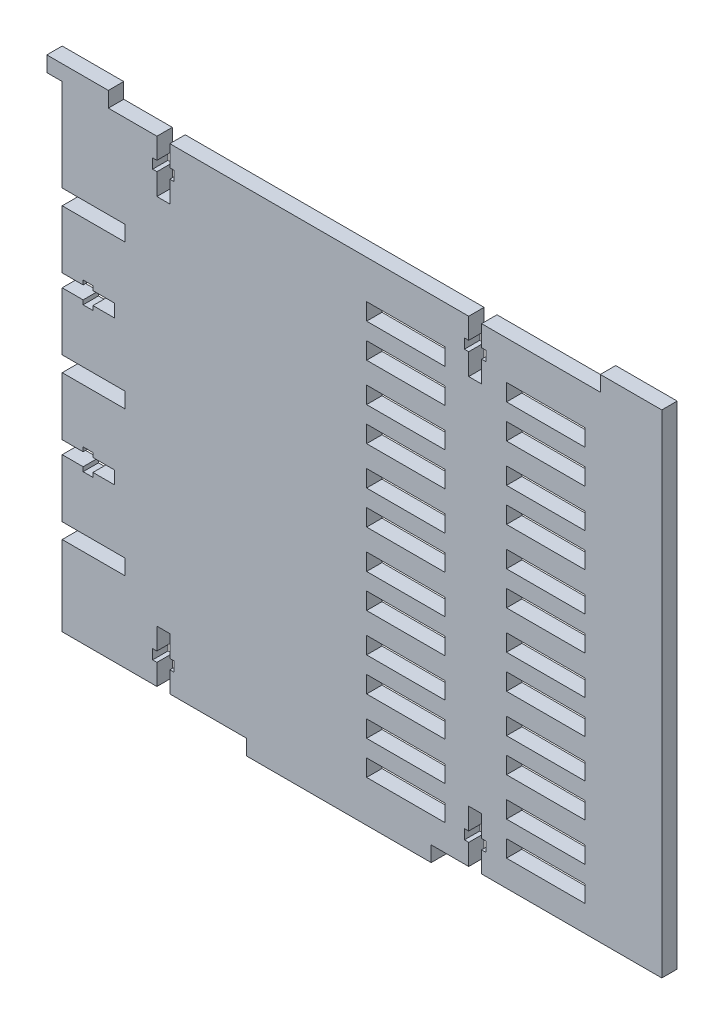
SolidWorks part; units mm, degrees
ref_plane "Front Plane" through (0, 0, 0) normal (0, 0, 1) x (1, 0, 0)
ref_plane "Top Plane" through (0, 0, 0) normal (0, 1, 0) x (1, 0, 0)
ref_plane "Right Plane" through (0, 0, 0) normal (1, 0, 0) x (0, 0, -1)
sketch "Sketch1" plane through (0, 0, 0) normal (0, 0, 1) x (1, 0, 0)
  line L0 (-45.5, 11) -> (-45.5, 16.5)
  line L1 (0, 0) -> (-25.5, 0)
  line L2 (0, 0) -> (0, 5.5)
  line L3 (0, 5.5) -> (-25.5, 5.5)
  line L4 (-25.5, 0) -> (-25.5, 5.5)
  line L5 (-45.5, 0) -> (-71, 0)
  line L6 (-45.5, 0) -> (-45.5, 5.5)
  line L7 (-45.5, 5.5) -> (-71, 5.5)
  line L8 (-71, 0) -> (-71, 5.5)
  line L9 (-45.5, 11) -> (-71, 11)
  line L10 (-71, 11) -> (-71, 16.5)
  line L11 (-45.5, 16.5) -> (-71, 16.5)
  line L12 (0, 11) -> (0, 16.5)
  line L13 (0, 11) -> (-25.5, 11)
  line L14 (-25.5, 11) -> (-25.5, 16.5)
  line L15 (0, 16.5) -> (-25.5, 16.5)
  line L16 (0, 23.5) -> (0, 29)
  line L17 (0, 23.5) -> (-25.5, 23.5)
  line L18 (-25.5, 23.5) -> (-25.5, 29)
  line L19 (0, 29) -> (-25.5, 29)
  line L20 (-45.5, 23.5) -> (-45.5, 29)
  line L21 (-45.5, 23.5) -> (-71, 23.5)
  line L22 (-71, 23.5) -> (-71, 29)
  line L23 (-45.5, 29) -> (-71, 29)
  line L24 (-45.5, 34.5) -> (-45.5, 40)
  line L25 (-45.5, 40) -> (-71, 40)
  line L26 (-71, 34.5) -> (-71, 40)
  line L27 (-45.5, 34.5) -> (-71, 34.5)
  line L28 (0, 34.5) -> (0, 40)
  line L29 (0, 40) -> (-25.5, 40)
  line L30 (-25.5, 34.5) -> (-25.5, 40)
  line L31 (0, 34.5) -> (-25.5, 34.5)
  line L32 (0, 47) -> (0, 52.5)
  line L33 (0, 47) -> (-25.5, 47)
  line L34 (-25.5, 47) -> (-25.5, 52.5)
  line L35 (0, 52.5) -> (-25.5, 52.5)
  line L36 (-45.5, 47) -> (-45.5, 52.5)
  line L37 (-45.5, 47) -> (-71, 47)
  line L38 (-71, 47) -> (-71, 52.5)
  line L39 (-45.5, 52.5) -> (-71, 52.5)
  line L40 (-45.5, 58) -> (-45.5, 63.5)
  line L41 (-45.5, 63.5) -> (-71, 63.5)
  line L42 (-71, 58) -> (-71, 63.5)
  line L43 (-45.5, 58) -> (-71, 58)
  line L44 (0, 58) -> (0, 63.5)
  line L45 (0, 63.5) -> (-25.5, 63.5)
  line L46 (-25.5, 58) -> (-25.5, 63.5)
  line L47 (0, 58) -> (-25.5, 58)
  line L48 (0, 70.5) -> (0, 76)
  line L49 (0, 70.5) -> (-25.5, 70.5)
  line L50 (-25.5, 70.5) -> (-25.5, 76)
  line L51 (0, 76) -> (-25.5, 76)
  line L52 (-45.5, 70.5) -> (-45.5, 76)
  line L53 (-45.5, 70.5) -> (-71, 70.5)
  line L54 (-71, 70.5) -> (-71, 76)
  line L55 (-45.5, 76) -> (-71, 76)
  line L56 (-45.5, 81.5) -> (-45.5, 87)
  line L57 (-45.5, 87) -> (-71, 87)
  line L58 (-71, 81.5) -> (-71, 87)
  line L59 (-45.5, 81.5) -> (-71, 81.5)
  line L60 (0, 81.5) -> (0, 87)
  line L61 (0, 87) -> (-25.5, 87)
  line L62 (-25.5, 81.5) -> (-25.5, 87)
  line L63 (0, 81.5) -> (-25.5, 81.5)
  line L64 (0, 94) -> (0, 99.5)
  line L65 (0, 94) -> (-25.5, 94)
  line L66 (-25.5, 94) -> (-25.5, 99.5)
  line L67 (0, 99.5) -> (-25.5, 99.5)
  line L68 (-45.5, 94) -> (-45.5, 99.5)
  line L69 (-45.5, 94) -> (-71, 94)
  line L70 (-71, 94) -> (-71, 99.5)
  line L71 (-45.5, 99.5) -> (-71, 99.5)
  line L72 (-45.5, 105) -> (-45.5, 110.5)
  line L73 (-45.5, 110.5) -> (-71, 110.5)
  line L74 (-71, 105) -> (-71, 110.5)
  line L75 (-45.5, 105) -> (-71, 105)
  line L76 (0, 105) -> (0, 110.5)
  line L77 (0, 110.5) -> (-25.5, 110.5)
  line L78 (-25.5, 105) -> (-25.5, 110.5)
  line L79 (0, 105) -> (-25.5, 105)
  line L80 (0, 117.5) -> (0, 123)
  line L81 (0, 117.5) -> (-25.5, 117.5)
  line L82 (-25.5, 117.5) -> (-25.5, 123)
  line L83 (0, 123) -> (-25.5, 123)
  line L84 (-45.5, 117.5) -> (-45.5, 123)
  line L85 (-45.5, 117.5) -> (-71, 117.5)
  line L86 (-71, 117.5) -> (-71, 123)
  line L87 (-45.5, 123) -> (-71, 123)
  line L88 (-45.5, 128.5) -> (-45.5, 134)
  line L89 (-45.5, 134) -> (-71, 134)
  line L90 (-71, 128.5) -> (-71, 134)
  line L91 (-45.5, 128.5) -> (-71, 128.5)
  line L92 (0, 128.5) -> (0, 134)
  line L93 (0, 134) -> (-25.5, 134)
  line L94 (-25.5, 128.5) -> (-25.5, 134)
  line L95 (0, 128.5) -> (-25.5, 128.5)
  line L96 (-155, 151.5) -> (-155, 146.5)
  line L97 (-175, 151.5) -> (-155, 151.5)
  line L98 (-175, 151.5) -> (-175, 146.5)
  line L100 (25, 151.5) -> (25, -8.5)
  line L101 (-155, 146.5) -> (5, 146.5)
  line L102 (5, 146.5) -> (5, 151.5)
  line L103 (-150, 71.5) -> (25, 71.5) construction
  line L107 (5, 151.5) -> (25, 151.5)
  line L109 (-175, 146.5) -> (-170, 146.5)
  line L110 (-170, 146.5) -> (-170, 116.5)
  line L113 (-170, 116.5) -> (-150, 116.5)
  line L114 (-150, 116.5) -> (-150, 111.5)
  line L115 (-150, 111.5) -> (-170, 111.5)
  line L116 (-170, 111.5) -> (-170, 92.6)
  line L120 (-150, 64.5) -> (-170, 64.5)
  line L121 (-170, 69.5) -> (-150, 69.5)
  line L122 (-150, 69.5) -> (-150, 64.5)
  line L126 (-150, 17.5) -> (-170, 17.5)
  line L127 (-170, 22.5) -> (-150, 22.5)
  line L128 (-150, 22.5) -> (-150, 17.5)
  line L133 (-170, 64.5) -> (-170, 46)
  line L134 (-170, 41) -> (-170, 22.5)
  line L135 (-170, 17.5) -> (-170, -8.5)
  line L137 (-170, -8.5) -> (25, -8.5)
  line L142 (-150, 88) -> (-170, 88) [skipped]
  line L143 (-150, 93) -> (-150, 88) [skipped]
  line L144 (-170, 93) -> (-150, 93) [skipped]
  line L145 (-170, 92.6) -> (-163.2, 92.6)
  line L146 (-163.2, 92.6) -> (-163.2, 94)
  line L147 (-163.2, 94) -> (-160, 94)
  line L148 (-160, 94) -> (-160, 92.6)
  line L149 (-160, 92.6) -> (-153, 92.6)
  line L150 (-153, 92.6) -> (-153, 88.4)
  line L151 (-153, 88.4) -> (-160, 88.4)
  line L152 (-160, 88.4) -> (-160, 87)
  line L153 (-160, 87) -> (-163.2, 87)
  line L154 (-163.2, 87) -> (-163.2, 88.4)
  line L155 (-163.2, 88.4) -> (-170, 88.4)
  line L157 (-170, 88.4) -> (-170, 69.5)
  line L158 (-163.2, 41.4) -> (-170, 41.4)
  line L159 (-170, 45.6) -> (-163.2, 45.6)
  line L160 (-163.2, 45.6) -> (-163.2, 47)
  line L161 (-163.2, 40) -> (-163.2, 41.4)
  line L162 (-160, 40) -> (-163.2, 40)
  line L163 (-160, 41.4) -> (-160, 40)
  line L164 (-153, 41.4) -> (-160, 41.4)
  line L165 (-160, 45.6) -> (-153, 45.6)
  line L166 (-153, 45.6) -> (-153, 41.4)
  line L167 (-160, 47) -> (-160, 45.6)
  line L168 (-163.2, 47) -> (-160, 47)
  line L180 (-170, 46) -> (-170, 45.6)
  line L181 (-170, 41.4) -> (-170, 41)
  line L185 (-150, -6) -> (-170, -6) [skipped]
  line L186 (-170, -1) -> (-150, -1) [skipped]
  line L187 (-150, -1) -> (-150, -6) [skipped]
  line L188 (-150, 41) -> (-170, 41) [skipped]
  line L189 (-150, 46) -> (-150, 41) [skipped]
  line L190 (-170, 46) -> (-150, 46) [skipped]
  line L191 (-163.2, -5.6) -> (-170, -5.6) [skipped]
  line L192 (-170, -1.4) -> (-163.2, -1.4) [skipped]
  line L193 (-163.2, 0) -> (-160, 0) [skipped]
  line L194 (-160, -1.4) -> (-153, -1.4) [skipped]
  line L195 (-160, 0) -> (-160, -1.4) [skipped]
  line L196 (-163.2, -1.4) -> (-163.2, 0) [skipped]
  line L197 (-163.2, -7) -> (-163.2, -5.6) [skipped]
  line L198 (-160, -7) -> (-163.2, -7) [skipped]
  line L199 (-160, -5.6) -> (-160, -7) [skipped]
  line L200 (-153, -5.6) -> (-160, -5.6) [skipped]
  line L201 (-153, -1.4) -> (-153, -5.6) [skipped]
  point P120 (-156.5, 88.4)
  point P124 (-163.2, 87.7)
  point P130 (-150, 114)
  point P131 (-153, 90.5)
  point P138 (-170, -3.3832)
  dimension "D1" = 25.5
  dimension "D2" = 25.5
  dimension "D3" = 20
  dimension "D4" = 5.5
  dimension "D5" = 5.5
  dimension "D7" = 11
  dimension "D9" = 200
  dimension "D10" = 25
  dimension "D11" = 4.2
  dimension "D12" = 23
  dimension "D13" = 128.5
  dimension "D14" = 5
  dimension "D15" = 20
  dimension "D16" = 20
  dimension "D17" = 5
  dimension "D18" = 155
  dimension "D19" = 155
  dimension "D20" = 3.2
  dimension "D21" = 5
  dimension "D22" = 20
  dimension "D23" = 30
  dimension "D24" = 6
  dimension "D25" = 3.2
  dimension "D26" = 7
  dimension "D27" = 4.2
  dimension "D28" = 17
  dimension "D29" = 6.8
  dimension "D30" = 6.8
  dimension "D6" = 2
  dimension "D8" = 6
  dimension "D31" = 3
extrude "Boss-Extrude1" add sketch "Sketch1" along normal blind 5
sketch "Sketch4" plane through (0, 0, 5) normal (0, 0, 1) x (1, 0, 0)
  line L0 (25, -8.5) -> (25, 151.5) construction
  line L1 (-170, -8.5) -> (25, -8.5) construction
  line L2 (-170, 146.5) -> (-170, 116.5) construction
  line L3 (-37.8, 129.5) -> (-37.8, 136.5)
  line L4 (-37.8, 139.7) -> (-37.8, 146.5)
  line L5 (-33.6, 146.5) -> (-33.6, 139.7)
  line L6 (-32.2, 139.7) -> (-32.2, 136.5)
  line L7 (-32.2, 136.5) -> (-33.6, 136.5)
  line L8 (-33.6, 139.7) -> (-32.2, 139.7)
  line L9 (-39.2, 139.7) -> (-37.8, 139.7)
  line L10 (-39.2, 136.5) -> (-39.2, 139.7)
  line L11 (-139.2, 139.7) -> (-139.2, 146.5)
  line L12 (-140.6, 139.7) -> (-139.2, 139.7)
  line L13 (-140.6, 136.5) -> (-140.6, 139.7)
  line L14 (-139.2, 136.5) -> (-140.6, 136.5)
  line L15 (-139.2, 129.5) -> (-139.2, 136.5)
  line L16 (-135, 129.5) -> (-139.2, 129.5)
  line L17 (-135, 136.5) -> (-135, 129.5)
  line L18 (-133.6, 136.5) -> (-135, 136.5)
  line L19 (-133.6, 139.7) -> (-133.6, 136.5)
  line L20 (-135, 139.7) -> (-133.6, 139.7)
  line L21 (-135, 146.5) -> (-135, 139.7)
  line L22 (-37.8, 136.5) -> (-39.2, 136.5)
  line L23 (-33.6, 136.5) -> (-33.6, 129.5)
  line L24 (-33.6, 129.5) -> (-37.8, 129.5)
  line L25 (-139.2, 146.5) -> (-135, 146.5)
  line L26 (-37.8, 146.5) -> (-33.6, 146.5)
  line L31 (-170, 69) -> (25, 69) construction
  line L32 (-170, 88.4) -> (-170, 69.5) construction
  line L33 (5, 146.5) -> (-155, 146.5) construction
  line L34 (-37.8, -8.5) -> (-33.6, -8.5)
  line L35 (-139.2, -8.5) -> (-135, -8.5)
  line L36 (-33.6, 8.5) -> (-37.8, 8.5)
  line L37 (-33.6, 1.5) -> (-33.6, 8.5)
  line L38 (-37.8, 1.5) -> (-39.2, 1.5)
  line L39 (-135, -8.5) -> (-135, -1.7)
  line L40 (-135, -1.7) -> (-133.6, -1.7)
  line L41 (-133.6, -1.7) -> (-133.6, 1.5)
  line L42 (-133.6, 1.5) -> (-135, 1.5)
  line L43 (-135, 1.5) -> (-135, 8.5)
  line L44 (-135, 8.5) -> (-139.2, 8.5)
  line L45 (-139.2, 8.5) -> (-139.2, 1.5)
  line L46 (-139.2, 1.5) -> (-140.6, 1.5)
  line L47 (-140.6, 1.5) -> (-140.6, -1.7)
  line L48 (-140.6, -1.7) -> (-139.2, -1.7)
  line L49 (-139.2, -1.7) -> (-139.2, -8.5)
  line L50 (-39.2, 1.5) -> (-39.2, -1.7)
  line L51 (-39.2, -1.7) -> (-37.8, -1.7)
  line L52 (-33.6, -1.7) -> (-32.2, -1.7)
  line L53 (-32.2, 1.5) -> (-33.6, 1.5)
  line L54 (-32.2, -1.7) -> (-32.2, 1.5)
  line L55 (-33.6, -8.5) -> (-33.6, -1.7)
  line L56 (-37.8, -1.7) -> (-37.8, -8.5)
  line L57 (-37.8, 8.5) -> (-37.8, 1.5)
  point P6 (-139.2, 143.1)
  dimension "D1" = 4.2
  dimension "D2" = 30.8
  dimension "D3" = 2
extrude "Cut-Extrude1" cut sketch "Sketch4" against normal blind 10
sketch "Sketch5" plane through (0, 0, 0) normal (0, 0, -1) x (-1, 0, 0)
  line L0 (135, -8.5) -> (37.8, -8.5) construction
  line L1 (50, -8.5) -> (110, -8.5)
  line L2 (50, -8.5) -> (50, -13.5)
  line L3 (50, -13.5) -> (110, -13.5)
  line L4 (110, -8.5) -> (110, -13.5)
  line L5 (-25, -8.5) -> (-25, 151.5) construction
  line L7 (170, 17.5) -> (170, -8.5) construction
  dimension "D1" = 5
  dimension "D2" = 75
  dimension "D3" = 60
extrude "Boss-Extrude2" add sketch "Sketch5" against normal blind 5
sketch "Sketch6" plane through (0, 0, 0) normal (0, 0, -1) x (-1, 0, 0)
  line L0 (170, 111.5) -> (170, 92.6) construction
  line L1 (170, 116.5) -> (149.6, 116.5)
  line L2 (170, 116.5) -> (170, 111.5)
  line L3 (170, 111.5) -> (149.6, 111.5)
  line L4 (149.6, 116.5) -> (149.6, 111.5)
  line L5 (153, 90.5) -> (132.7732, 90.5) construction
  line L6 (153, 92.6) -> (153, 88.4) construction
  line L7 (149.6, 64.5) -> (149.6, 69.5)
  line L8 (170, 69.5) -> (149.6, 69.5)
  line L9 (170, 64.5) -> (170, 69.5)
  line L10 (170, 64.5) -> (149.6, 64.5)
  line L11 (153, 43.5) -> (121.2452, 43.5) construction
  line L12 (153, 45.6) -> (153, 41.4) construction
  line L13 (170, 22.5) -> (149.6, 22.5)
  line L14 (170, 22.5) -> (170, 17.5)
  line L15 (170, 17.5) -> (149.6, 17.5)
  line L16 (149.6, 22.5) -> (149.6, 17.5)
  dimension "D1" = 20.4
  dimension "D2" = 5
extrude "Cut-Extrude2" cut sketch "Sketch6" against normal blind 10
